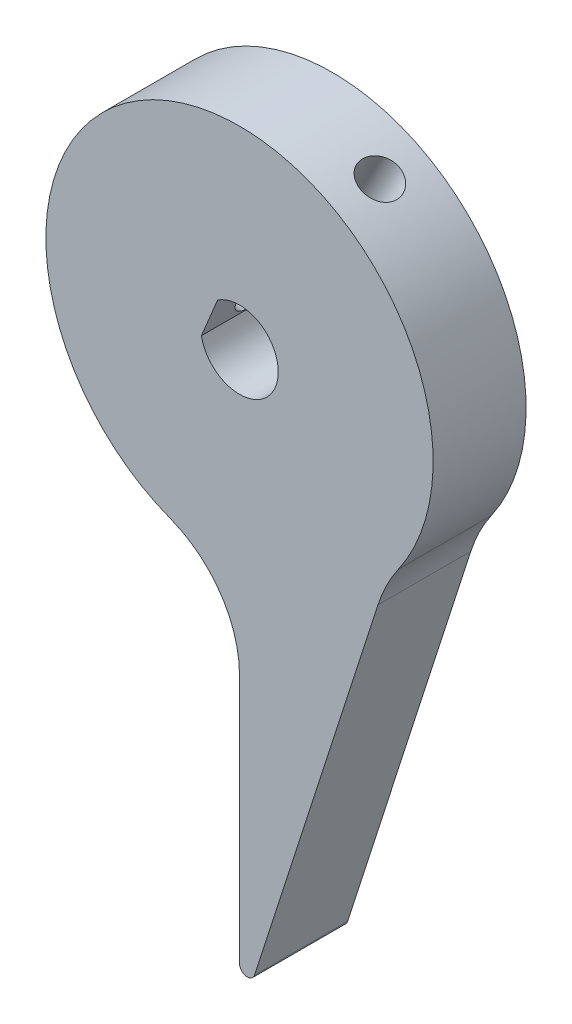
SolidWorks part; units mm, degrees
ref_plane "正面" through (0, 0, 0) normal (0, 0, 1) x (1, 0, 0)
ref_plane "平面" through (0, 0, 0) normal (0, 1, 0) x (1, 0, 0)
ref_plane "右側面" through (0, 0, 0) normal (1, 0, 0) x (0, 0, -1)
sketch "ｽｹｯﾁ1" plane through (0, 0, 0) normal (0, 0, 1) x (1, 0, 0)
  line L0 (0, -12.5) -> (0, -37.5)
  line L1 (0, -37.5) -> (9.4628, -8.1673)
  arc A0 (9.4628, -8.1673) -> (0, -12.5) centre (0, 0) ccw
  point P7 (9.4628, -8.1673)
  point P9 (0, -12.5)
  dimension "D1" = 37.5
  dimension "D2" = 25
extrude "ﾎﾞｽ - 押し出し1" add sketch "ｽｹｯﾁ1" along normal blind 6
fillet "ﾌｨﾚｯﾄ1" radius 7 1 edges at (0, -12.5, 3)
fillet "ﾌｨﾚｯﾄ2" radius 10 1 edges at (9.4628, -8.1673, 3)
fillet "ﾌｨﾚｯﾄ5" radius 0.5 1 edges at (0, -37.5, 3)
sketch "ｽｹｯﾁ2" plane through (0, 0, 0) normal (0, 0, -1) x (-1, 0, 0)
  line L0 (1.419, 2.0582) -> (2.4597, -0.4472)
  line L1 (1.9394, 0.8055) -> (-2.3088, -0.959) construction
  arc A0 (1.419, 2.0582) -> (2.4597, -0.4472) centre (0, 0) ccw
  point P1 (-2.2522, -1.0852)
  point P7 (-2.0802, -1.3867)
  point P8 (-2.3383, -0.8845)
  point P9 (-2.3088, -0.959)
  dimension "D1" = 5
  dimension "D2" = 4.6
extrude "ｶｯﾄ - 押し出し1" cut sketch "ｽｹｯﾁ2" against normal up to next
sketch "ｽｹｯﾁ10" plane through (0, 0, 6) normal (0, 0, 1) x (1, 0, 0)
  arc A0 (10.2506, -7.1537) -> (-4.4872, -11.6668) centre (0, 0) ccw construction
  point P0 (-12.0586, 3.2926)
ref_plane "平面2" through (-12.0586, 3.2926, 6) normal (-0.9647, 0.2634, 0) x (0, 0, 1)
hole_wizard "M3x0.5 ねじ穴10" positions "ｽｹｯﾁ15" profile "ｽｹｯﾁ16" tap size "M3x0.5" standard "JIS"
sketch "ｽｹｯﾁ15" plane through (-12.0586, 3.2926, 6) normal (-0.9647, 0.2634, 0) x (0, 0, 1)
  point P0 (-2.9972, 0.2455)
sketch "ｽｹｯﾁ16" plane through (-11.9939, 3.5294, 3.0028) normal (0, 0, 1) x (-0.2634, -0.9647, 0)
  line L0 (0, 0) -> (0, 10.4143)
  line L1 (0, 10.4143) -> (1.25, 10.4143)
  line L2 (1.25, 10.4143) -> (1.25, 0)
  line L5 (1.25, 0) -> (0, 0)
  line L11 (0, -6.35) -> (0, 107.95) construction
  dimension "ねじ山の主要直径" = 2.5
  dimension "次ｻｰﾌｪｽまでのねじ下穴ﾄﾞﾘﾙの深さ" = 10.4143
sketch "ｽｹｯﾁ19" plane through (0, 0, 0) normal (0, 0, -1) x (-1, 0, 0)
  arc A0 (4.4872, -11.6668) -> (-10.2506, -7.1537) centre (0, 0) ccw construction
  point P0 (-5.9588, 10.9883)
ref_plane "平面3" through (5.9588, 10.9883, 0) normal (0.4767, 0.8791, 0) x (0.8791, -0.4767, 0)
hole_wizard "M3x0.5 ねじ穴9" positions "ｽｹｯﾁ24" profile "ｽｹｯﾁ25" tap size "M3x0.5" standard "JIS"
sketch "ｽｹｯﾁ24" plane through (5.9588, 10.9883, 0) normal (0.4767, 0.8791, 0) x (0.8791, -0.4767, 0)
  point P0 (0, -2.8856)
sketch "ｽｹｯﾁ25" plane through (5.9588, 10.9883, 2.8856) normal (0, 0, 1) x (-0.8791, 0.4767, 0)
  line L0 (0, 0) -> (0, 10)
  line L1 (0, 10) -> (1.25, 10)
  line L2 (1.25, 10) -> (1.25, 0)
  line L5 (1.25, 0) -> (0, 0)
  line L11 (0, -6.35) -> (0, 107.95) construction
  dimension "次ｻｰﾌｪｽまでのねじ下穴ﾄﾞﾘﾙ直径" = 2.5
  dimension "次ｻｰﾌｪｽまでのねじ下穴ﾄﾞﾘﾙの深さ" = 10
cosmetic thread "穴のねじ山4" parameters "D2"=3
